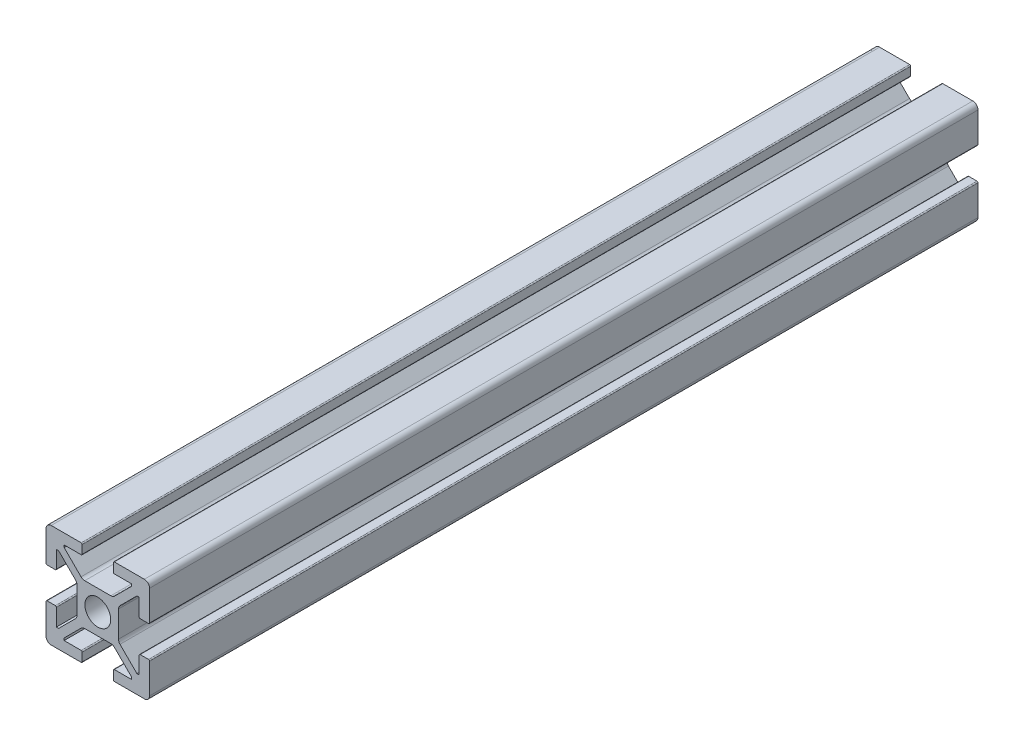
SolidWorks part; units mm, degrees
ref_plane "Front Plane" through (0, 0, 0) normal (0, 0, 1) x (1, 0, 0)
ref_plane "Top Plane" through (0, 0, 0) normal (0, 1, 0) x (1, 0, 0)
ref_plane "Right Plane" through (0, 0, 0) normal (1, 0, 0) x (0, 0, -1)
sketch "Sketch1" plane through (0, 0, 0) normal (0, 0, 1) x (1, 0, 0)
  line L0 (0.2, 13) -> (1.8, 13)
  line L1 (13.2, 0) -> (19, 0)
  line L2 (0, 13.2) -> (0, 19)
  line L3 (1, 20) -> (6.8, 20)
  line L4 (20, 1) -> (20, 6.8)
  line L5 (2, 13.2) -> (2, 16.5)
  line L6 (2, 16.5) -> (2.4393, 16.5)
  line L7 (2.4393, 16.5) -> (5.7071, 13.2322)
  line L8 (6, 12.5251) -> (6, 7.4749)
  line L11 (7.4749, 14) -> (10, 14)
  line L12 (3.5, 17.5607) -> (6.7678, 14.2929)
  line L13 (3.5, 18) -> (3.5, 17.5607)
  line L14 (6.8, 18) -> (3.5, 18)
  line L15 (6.8, 20) -> (1, 20)
  line L16 (7, 19.8) -> (7, 18.2)
  line L17 (19.8, 7) -> (18.2, 7)
  line L18 (20, 6.8) -> (20, 1)
  line L19 (18, 6.8) -> (18, 3.5)
  line L20 (18, 3.5) -> (17.5607, 3.5)
  line L21 (17.5607, 3.5) -> (14.2929, 6.7678)
  line L22 (14, 7.4749) -> (14, 12.5251)
  line L23 (12.5251, 6) -> (10, 6)
  line L24 (16.5, 2.4393) -> (13.2322, 5.7071)
  line L25 (16.5, 2) -> (16.5, 2.4393)
  line L26 (13.2, 2) -> (16.5, 2)
  line L27 (13.2, 0) -> (19, 0)
  line L28 (13, 0.2) -> (13, 1.8)
  line L30 (13, 19.8) -> (13, 18.2)
  line L31 (13.2, 20) -> (19, 20)
  line L32 (13.2, 18) -> (16.5, 18)
  line L33 (16.5, 18) -> (16.5, 17.5607)
  line L34 (16.5, 17.5607) -> (13.2322, 14.2929)
  line L35 (12.5251, 14) -> (10, 14)
  line L36 (17.5607, 16.5) -> (14.2929, 13.2322)
  line L37 (18, 16.5) -> (17.5607, 16.5)
  line L38 (18, 13.2) -> (18, 16.5)
  line L39 (20, 13.2) -> (20, 19)
  line L40 (19.8, 13) -> (18.2, 13)
  line L41 (7, 0.2) -> (7, 1.8)
  line L42 (6.8, 0) -> (1, 0)
  line L43 (6.8, 2) -> (3.5, 2)
  line L44 (3.5, 2) -> (3.5, 2.4393)
  line L45 (3.5, 2.4393) -> (6.7678, 5.7071)
  line L46 (7.4749, 6) -> (10, 6)
  line L47 (2.4393, 3.5) -> (5.7071, 6.7678)
  line L48 (2, 3.5) -> (2.4393, 3.5)
  line L49 (2, 6.8) -> (2, 3.5)
  line L50 (20, 19) -> (20, 13.2)
  line L51 (1, 0) -> (6.8, 0)
  line L52 (0, 6.8) -> (0, 1)
  line L53 (13.2, 20) -> (19, 20)
  line L54 (0.2, 7) -> (1.8, 7)
  arc A0 (20, 1) -> (19, 0) centre (19, 1) cw
  arc A1 (1, 0) -> (0, 1) centre (1, 1) cw
  arc A2 (0, 19) -> (1, 20) centre (1, 19) cw
  arc A3 (20, 19) -> (19, 20) centre (19, 19) ccw
  arc A4 (14.2929, 6.7678) -> (14, 7.4749) centre (15, 7.4749) cw
  arc A5 (12.5251, 6) -> (13.2322, 5.7071) centre (12.5251, 5) cw
  arc A6 (6.7678, 5.7071) -> (7.4749, 6) centre (7.4749, 5) cw
  arc A7 (5.7071, 6.7678) -> (6, 7.4749) centre (5, 7.4749) ccw
  arc A8 (14.2929, 13.2322) -> (14, 12.5251) centre (15, 12.5251) ccw
  arc A9 (13.2322, 14.2929) -> (12.5251, 14) centre (12.5251, 15) cw
  arc A10 (6, 12.5251) -> (5.7071, 13.2322) centre (5, 12.5251) ccw
  arc A11 (7.4749, 14) -> (6.7678, 14.2929) centre (7.4749, 15) cw
  arc A12 (0, 6.8) -> (0.2, 7) centre (0.2, 6.8) cw
  arc A13 (2, 6.8) -> (1.8, 7) centre (1.8, 6.8) ccw
  arc A14 (7, 1.8) -> (6.8, 2) centre (6.8, 1.8) ccw
  arc A15 (7, 0.2) -> (6.8, 0) centre (6.8, 0.2) cw
  arc A16 (13.2, 0) -> (13, 0.2) centre (13.2, 0.2) cw
  arc A17 (13.2, 2) -> (13, 1.8) centre (13.2, 1.8) ccw
  arc A18 (18.2, 7) -> (18, 6.8) centre (18.2, 6.8) ccw
  arc A19 (19.8, 7) -> (20, 6.8) centre (19.8, 6.8) cw
  arc A20 (20, 13.2) -> (19.8, 13) centre (19.8, 13.2) cw
  arc A21 (18, 13.2) -> (18.2, 13) centre (18.2, 13.2) ccw
  arc A22 (13, 19.8) -> (13.2, 20) centre (13.2, 19.8) cw
  arc A23 (13, 18.2) -> (13.2, 18) centre (13.2, 18.2) ccw
  arc A24 (6.8, 18) -> (7, 18.2) centre (6.8, 18.2) ccw
  arc A25 (7, 19.8) -> (6.8, 20) centre (6.8, 19.8) ccw
  arc A26 (1.8, 13) -> (2, 13.2) centre (1.8, 13.2) ccw
  arc A27 (0.2, 13) -> (0, 13.2) centre (0.2, 13.2) cw
  circle A28 centre (10, 10) radius 2.5
  point P19 (2, 13)
  dimension "D1" = 1
  dimension "D4" = 1
  dimension "D5" = 0.2
  dimension "D6" = 0.2
  dimension "D7" = 5
  dimension "D2" = 7
  dimension "D3" = 2
  dimension "D9" = 3.5
extrude "Boss-Extrude1" add sketch "Sketch1" along normal blind 160 contours A27 L0 A26 L5 L6 L7 A10 L8 A7 L47 L48 L49 A13 L54 A12 L52 A1 L42 A15 L41 A14 L43 L44 L45 A6 L46 L23 A5 L24 L25 L26 A17 L28 A16 L1 A0 L4 A19 L17 A18 L19 L20 L21 A4 L22 A8 L36 L37 L38 A21 L40
